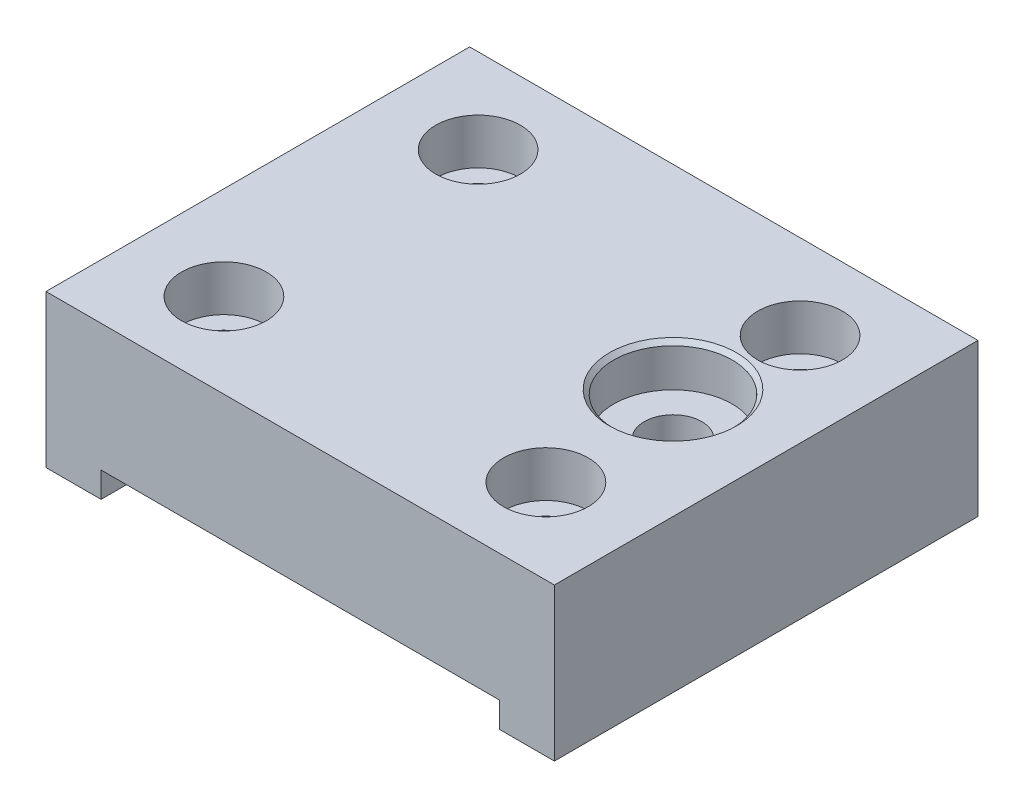
SolidWorks part; units mm, degrees
ref_plane "Front Plane" through (0, 0, 0) normal (0, 0, 1) x (1, 0, 0)
ref_plane "Top Plane" through (0, 0, 0) normal (0, 1, 0) x (1, 0, 0)
ref_plane "Right Plane" through (0, 0, 0) normal (1, 0, 0) x (0, 0, -1)
sketch "Sketch1" plane through (0, 0, 0) normal (0, 1, 0) x (1, 0, 0)
  line L1 (-30, 25) -> (30, 25)
  line L2 (-30, 25) -> (-30, -25)
  line L3 (-30, -25) -> (30, -25)
  line L4 (30, 25) -> (30, -25)
  line L5 (-30, 25) -> (30, -25) construction
  line L6 (-30, -25) -> (30, 25) construction
  point P0 (0, 0)
  dimension "D1" = 60
  dimension "D2" = 50
extrude "Boss-Extrude1" add sketch "Sketch1" along normal mid plane 18
sketch "Sketch2" plane through (0, 0, 25) normal (0, 0, 1) x (1, 0, 0)
  line L0 (-30, -9) -> (30, -9) construction
  line L1 (-23.5, -6) -> (23.5, -6)
  line L2 (-23.5, -6) -> (-23.5, -12)
  line L3 (-23.5, -12) -> (23.5, -12)
  line L4 (23.5, -6) -> (23.5, -12)
  point P7 (0, -6)
  dimension "D1" = 47
  dimension "D2" = 6
  dimension "D3" = 3
extrude "Cut-Extrude1" cut sketch "Sketch2" against normal through all
hole_wizard "CBORE for M5 Hex Socket Head Cap Screw1" positions "Sketch4" profile "Sketch3" counterbore size "M5" standard "ISO" end condition through all
sketch "Sketch4" plane through (0, 9, 0) normal (0, 1, 0) x (1, 0, 0)
  point P0 (-19, 15)
  point P2 (19, 15)
  point P4 (19, -15)
  point P6 (-19, -15)
  dimension "D1" = 30
  dimension "D2" = 38
  dimension "D3" = 19
  dimension "D4" = 15
sketch "Sketch3" plane through (-19, 9, -15) normal (1, 0, 0) x (0, 0, 1)
  line L0 (0, 0) -> (0, 18)
  line L1 (0, 18) -> (2.75, 18)
  line L3 (2.75, 18) -> (2.75, 5.4)
  line L4 (2.75, 5.4) -> (5, 5.4)
  line L5 (5, 5.4) -> (5, 0)
  line L7 (5, 0) -> (0, 0)
  line L11 (0, -6.35) -> (0, 107.95) construction
  dimension "Thru Hole Dia." = 5.5
  dimension "Thru Hole Depth" = 18
  dimension "C'Bore Dia." = 10
  dimension "C'Bore Depth" = 5.4
hole_wizard "M8 Tapped Hole1" positions "Sketch7" profile "Sketch8" tap size "M8" standard "ISO" end condition through all
sketch "Sketch7" plane through (0, 9, 0) normal (0, 1, 0) x (1, 0, 0)
  circle A0 centre (19, -15) radius 2.75 construction
  circle A1 centre (19, 15) radius 2.75 construction
  point P0 (17, 2)
  dimension "D2" = 2
  dimension "D1" = 17
sketch "Sketch8" plane through (17, 9, -2) normal (1, 0, 0) x (0, 0, 1)
  line L0 (0, 0) -> (0, 18)
  line L1 (0, 18) -> (3.4, 18)
  line L2 (3.4, 18) -> (3.4, 0)
  line L5 (3.4, 0) -> (0, 0)
  line L11 (0, -6.35) -> (0, 107.95) construction
  dimension "Thru Tap Drill Dia." = 6.8
  dimension "Thru Tap Drill Depth" = 18
cosmetic thread "Hole Thread1" parameters "D2"=8
sketch "Sketch9" plane through (0, 9, 0) normal (0, 1, 0) x (1, 0, 0)
  circle A0 centre (17, 2) radius 7
  circle A1 centre (17, 2) radius 3.4 construction
  dimension "D1" = 14
extrude "Cut-Extrude2" cut sketch "Sketch9" against normal blind 5
chamfer "Chamfer1" distance 0.5 angle 45 1 edges at (17, 9, 5)
